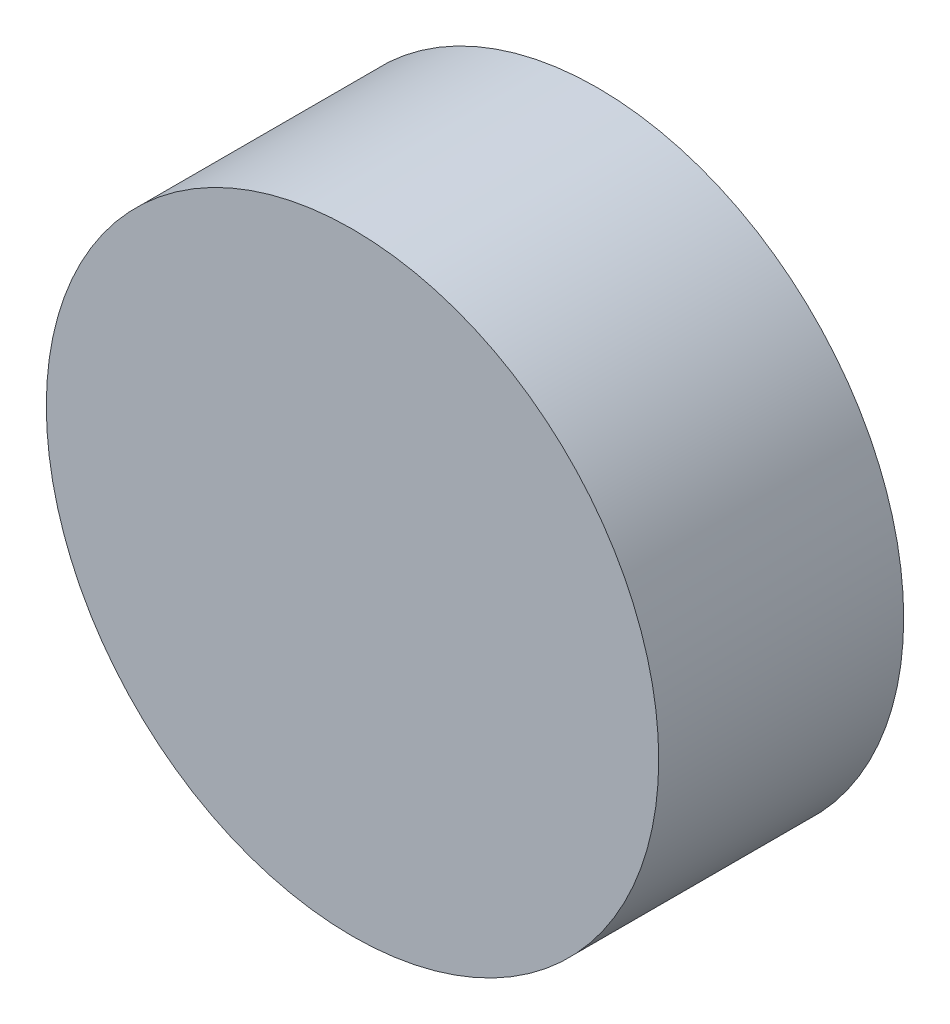
SolidWorks part; units mm, degrees
ref_plane "Front" through (0, 0, 0) normal (0, 0, 1) x (1, 0, 0)
ref_plane "Top" through (0, 0, 0) normal (0, 1, 0) x (1, 0, 0)
ref_plane "Right" through (0, 0, 0) normal (1, 0, 0) x (0, 0, -1)
sketch "Sketch1" plane through (0, 0, 0) normal (0, 0, 1) x (1, 0, 0)
  circle A0 centre (0, 0) radius 2.54
  dimension "D1" = 5.08
extrude "Boss-Extrude1" add sketch "Sketch1" along normal blind 2.032
sketch "Sketch2" plane through (0, 0, 2.032) normal (0, 0, 1) x (1, 0, 0)
  circle A0 centre (0, 0) radius 0.4445
  dimension "D1" = 0.889
